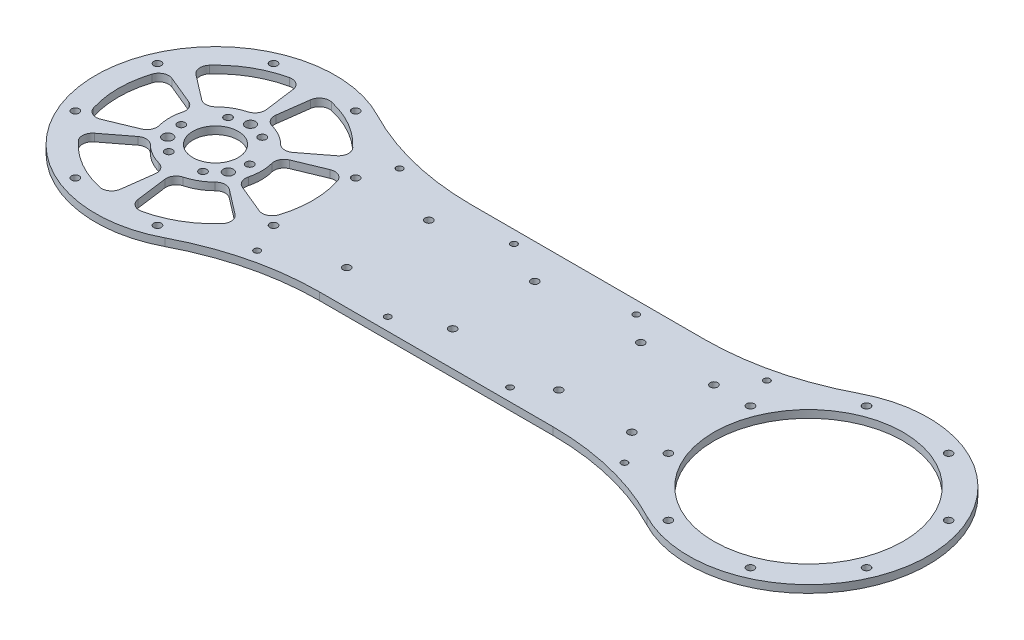
SolidWorks part; units mm, degrees
material "Hexcel AS4C (3000 丝)"
ref_plane "前视基准面" through (0, 0, 0) normal (0, 0, 1) x (1, 0, 0)
ref_plane "上视基准面" through (0, 0, 0) normal (0, 1, 0) x (1, 0, 0)
ref_plane "右视基准面" through (0, 0, 0) normal (1, 0, 0) x (0, 0, -1)
sketch "草图1" plane through (0, 0, 0) normal (0, 1, 0) x (1, 0, 0)
  line L0 (0, 0) -> (235, 0) construction
  line L1 (22, 42.0981) -> (22, -42.0981) construction
  line L2 (213, 42.0981) -> (213, -42.0981) construction
  line L3 (71.2712, 30) -> (163.7288, 30)
  line L4 (71.2712, -30) -> (163.7288, -30)
  line L14 (251.264, -39.2649) -> (274.2649, -16.264) construction
  line L15 (274.2649, -16.264) -> (274.2649, 16.264) construction
  line L16 (274.2649, 16.264) -> (251.264, 39.2649) construction
  line L17 (251.264, 39.2649) -> (218.736, 39.2649) construction
  line L18 (218.736, 39.2649) -> (195.7351, 16.264) construction
  line L19 (195.7351, 16.264) -> (195.7351, -16.264) construction
  line L20 (195.7351, -16.264) -> (218.736, -39.2649) construction
  line L21 (218.736, -39.2649) -> (251.264, -39.2649) construction
  line L30 (-16.264, 39.2649) -> (-39.2649, 16.264) construction
  line L31 (-39.2649, 16.264) -> (-39.2649, -16.264) construction
  line L32 (-39.2649, -16.264) -> (-16.264, -39.2649) construction
  line L33 (-16.264, -39.2649) -> (16.264, -39.2649) construction
  line L34 (16.264, -39.2649) -> (39.2649, -16.264) construction
  line L35 (39.2649, -16.264) -> (39.2649, 16.264) construction
  line L36 (39.2649, 16.264) -> (16.264, 39.2649) construction
  line L37 (16.264, 39.2649) -> (-16.264, 39.2649) construction
  line L38 (6.7839, -11.75) -> (13.5677, 0) construction
  line L39 (13.5677, 0) -> (6.7839, 11.75) construction
  line L40 (6.7839, 11.75) -> (-6.7839, 11.75) construction
  line L41 (-6.7839, 11.75) -> (-13.5677, 0) construction
  line L42 (-13.5677, 0) -> (-6.7839, -11.75) construction
  line L43 (-6.7839, -11.75) -> (6.7839, -11.75) construction
  line L44 (-12, -6.9282) -> (0, -13.8564) construction
  line L45 (0, -13.8564) -> (12, -6.9282) construction
  line L46 (12, -6.9282) -> (12, 6.9282) construction
  line L47 (12, 6.9282) -> (0, 13.8564) construction
  line L48 (0, 13.8564) -> (-12, 6.9282) construction
  line L49 (-12, 6.9282) -> (-12, -6.9282) construction
  circle A0 centre (0, 0) radius 47.5 construction
  circle A1 centre (235, 0) radius 47.5 construction
  arc A2 (22, 42.0981) -> (22, -42.0981) centre (0, 0) ccw
  arc A3 (213, 42.0981) -> (213, -42.0981) centre (235, 0) cw
  arc A4 (22, 42.0981) -> (71.2712, 30) centre (71.2712, 136.381) ccw
  arc A5 (22, -42.0981) -> (71.2712, -30) centre (71.2712, -136.381) cw
  arc A6 (163.7288, 30) -> (213, 42.0981) centre (163.7288, 136.381) ccw
  arc A7 (163.7288, -30) -> (213, -42.0981) centre (163.7288, -136.381) cw
  circle A8 centre (235, 0) radius 42.5 construction
  circle A9 centre (218.736, 39.2649) radius 1.5
  circle A10 centre (251.264, 39.2649) radius 1.5
  circle A11 centre (274.2649, 16.264) radius 1.5
  circle A12 centre (274.2649, -16.264) radius 1.5
  circle A13 centre (251.264, -39.2649) radius 1.5
  circle A14 centre (218.736, -39.2649) radius 1.5
  circle A15 centre (195.7351, -16.264) radius 1.5
  circle A16 centre (195.7351, 16.264) radius 1.5
  circle A17 centre (235, 0) radius 37.5
  circle A18 centre (0, 0) radius 42.5 construction
  circle A19 centre (-16.264, 39.2649) radius 1.5
  circle A20 centre (16.264, 39.2649) radius 1.5
  circle A21 centre (39.2649, 16.264) radius 1.5
  circle A22 centre (39.2649, -16.264) radius 1.5
  circle A23 centre (16.264, -39.2649) radius 1.5
  circle A24 centre (-16.264, -39.2649) radius 1.5
  circle A25 centre (-39.2649, -16.264) radius 1.5
  circle A26 centre (-39.2649, 16.264) radius 1.5
  circle A27 centre (0, 0) radius 9
  circle A28 centre (0, 0) radius 11.75 construction
  circle A29 centre (-6.7839, 11.75) radius 1.5
  circle A30 centre (6.7839, 11.75) radius 1.5
  circle A31 centre (13.5677, 0) radius 1.5
  circle A32 centre (6.7839, -11.75) radius 1.5
  circle A33 centre (-6.7839, -11.75) radius 1.5
  circle A34 centre (-13.5677, 0) radius 1.5
  circle A35 centre (0, 0) radius 12 construction
  circle A36 centre (0, 13.8564) radius 2
  circle A37 centre (-12, -6.9282) radius 2
  circle A38 centre (12, -6.9282) radius 2
  dimension "D2" = 95
  dimension "D6" = 85
  dimension "D7" = 3
  dimension "D8" = 75
  dimension "D9" = 85
  dimension "D10" = 3
  dimension "D11" = 18
  dimension "D12" = 23.5
  dimension "D13" = 3
  dimension "D15" = 4
  dimension "D1" = 235
  dimension "D3" = 22
  dimension "D4" = 22
  dimension "D5" = 60
  dimension "D14" = 24
extrude "凸台-拉伸1" add sketch "草图1" along normal blind 3
sketch "草图2" plane through (0, 0, 0) normal (0, -1, 0) x (1, 0, 0)
  circle A1 centre (0, 0) radius 9
  circle A2 centre (0, 0) radius 9
  circle A3 centre (235, 0) radius 29.6
  circle A4 centre (235, 0) radius 29.6
  circle A5 centre (218.736, -39.2649) radius 1.5
  circle A6 centre (218.736, -39.2649) radius 1.5
  circle A7 centre (251.264, -39.2649) radius 1.5
  circle A8 centre (251.264, -39.2649) radius 1.5
  circle A9 centre (251.264, 39.2649) radius 1.5
  circle A10 centre (251.264, 39.2649) radius 1.5
  circle A11 centre (274.2649, -16.264) radius 1.5
  circle A12 centre (274.2649, -16.264) radius 1.5
  circle A13 centre (274.2649, 16.264) radius 1.5
  circle A14 centre (274.2649, 16.264) radius 1.5
  circle A15 centre (195.7351, -16.264) radius 1.5
  circle A16 centre (195.7351, -16.264) radius 1.5
  circle A17 centre (195.7351, 16.264) radius 1.5
  circle A18 centre (195.7351, 16.264) radius 1.5
  circle A19 centre (218.736, 39.2649) radius 1.5
  circle A20 centre (218.736, 39.2649) radius 1.5
  circle A21 centre (-16.264, -39.2649) radius 1.5
  circle A22 centre (-16.264, -39.2649) radius 1.5
  circle A23 centre (16.264, -39.2649) radius 1.5
  circle A24 centre (16.264, -39.2649) radius 1.5
  circle A25 centre (39.2649, -16.264) radius 1.5
  circle A26 centre (39.2649, -16.264) radius 1.5
  circle A27 centre (39.2649, 16.264) radius 1.5
  circle A28 centre (39.2649, 16.264) radius 1.5
  circle A29 centre (16.264, 39.2649) radius 1.5
  circle A30 centre (16.264, 39.2649) radius 1.5
  circle A31 centre (-16.264, 39.2649) radius 1.5
  circle A32 centre (-16.264, 39.2649) radius 1.5
  circle A33 centre (-39.2649, 16.264) radius 1.5
  circle A34 centre (-39.2649, 16.264) radius 1.5
  circle A35 centre (-39.2649, -16.264) radius 1.5
  circle A36 centre (-39.2649, -16.264) radius 1.5
  circle A37 centre (6.7839, -11.75) radius 1.5
  circle A38 centre (6.7839, -11.75) radius 1.5
  circle A39 centre (13.5677, 0) radius 1.5
  circle A40 centre (13.5677, 0) radius 1.5
  circle A41 centre (-6.7839, -11.75) radius 1.5
  circle A42 centre (-6.7839, -11.75) radius 1.5
  circle A43 centre (-13.5677, 0) radius 1.5
  circle A44 centre (-13.5677, 0) radius 1.5
  circle A45 centre (6.7839, 11.75) radius 1.5
  circle A46 centre (6.7839, 11.75) radius 1.5
  circle A47 centre (-6.7839, 11.75) radius 1.5
  circle A48 centre (-6.7839, 11.75) radius 1.5
  circle A49 centre (93.2712, -25) radius 1.25
  circle A50 centre (93.2712, -25) radius 1.25
  circle A51 centre (93.2712, 25) radius 1.25
  circle A52 centre (93.2712, 25) radius 1.25
  circle A53 centre (190.2885, 28.213) radius 1.25
  circle A54 centre (190.2885, 28.213) radius 1.25
  circle A55 centre (141.7288, 25) radius 1.25
  circle A56 centre (141.7288, 25) radius 1.25
  circle A57 centre (44.7115, 28.213) radius 1.25
  circle A58 centre (44.7115, 28.213) radius 1.25
  circle A59 centre (44.7115, -28.213) radius 1.25
  circle A60 centre (44.7115, -28.213) radius 1.25
  circle A61 centre (190.2885, -28.213) radius 1.25
  circle A62 centre (190.2885, -28.213) radius 1.25
  circle A63 centre (141.7288, -25) radius 1.25
  circle A64 centre (141.7288, -25) radius 1.25
  dimension "D1" = 0
  dimension "D2" = 0
  dimension "D3" = 0
  dimension "D4" = 0
  dimension "D5" = 0
  dimension "D6" = 0
  dimension "D7" = 0
  dimension "D8" = 0
  dimension "D9" = 0
  dimension "D10" = 0
  dimension "D11" = 0
  dimension "D12" = 0
  dimension "D13" = 0
  dimension "D14" = 0
  dimension "D15" = 0
  dimension "D16" = 0
  dimension "D17" = 0
  dimension "D18" = 0
  dimension "D19" = 0
  dimension "D20" = 0
  dimension "D21" = 0
  dimension "D22" = 0
  dimension "D23" = 0
  dimension "D24" = 0
  dimension "D25" = 0
  dimension "D26" = 0
  dimension "D27" = 0
  dimension "D28" = 0
  dimension "D29" = 0
  dimension "D30" = 0
  dimension "D31" = 0
  dimension "D32" = 0
extrude "切除-拉伸1" cut sketch "草图2" against normal blind 10 contours A54 | A56 | A52 | A58 | A60 | A50 | A64 | A62
sketch "草图3" plane through (0, 0, 0) normal (0, -1, 0) x (1, 0, 0)
  line L2 (-3.4947, -34.2058) -> (-1.8862, -21.9887)
  line L3 (-18.0997, -12.6279) -> (-27.8758, -20.1294)
  line L4 (-3.4947, -34.2058) -> (-1.8862, -21.9887)
  line L5 (-18.0997, -12.6279) -> (-27.8758, -20.1294)
  line L6 (-31.3704, -14.0764) -> (-19.9859, -9.3608)
  line L7 (-19.9859, 9.3608) -> (-31.3704, 14.0764)
  line L8 (-31.3704, -14.0764) -> (-19.9859, -9.3608)
  line L9 (-19.9859, 9.3608) -> (-31.3704, 14.0764)
  line L10 (-27.8758, 20.1294) -> (-18.0997, 12.6279)
  line L11 (-1.8862, 21.9887) -> (-3.4947, 34.2058)
  line L12 (-27.8758, 20.1294) -> (-18.0997, 12.6279)
  line L13 (-1.8862, 21.9887) -> (-3.4947, 34.2058)
  line L14 (3.4947, 34.2058) -> (1.8862, 21.9887)
  line L15 (18.0997, 12.6279) -> (27.8758, 20.1294)
  line L16 (3.4947, 34.2058) -> (1.8862, 21.9887)
  line L17 (18.0997, 12.6279) -> (27.8758, 20.1294)
  line L18 (31.3704, 14.0764) -> (19.9859, 9.3608)
  line L19 (19.9859, -9.3608) -> (31.3704, -14.0764)
  line L20 (31.3704, 14.0764) -> (19.9859, 9.3608)
  line L21 (19.9859, -9.3608) -> (31.3704, -14.0764)
  line L22 (27.8758, -20.1294) -> (18.0997, -12.6279)
  line L23 (1.8862, -21.9887) -> (3.4947, -34.2058)
  line L24 (27.8758, -20.1294) -> (18.0997, -12.6279)
  line L25 (1.8862, -21.9887) -> (3.4947, -34.2058)
  circle A1 centre (-12, 6.9282) radius 3
  circle A2 centre (-12, 6.9282) radius 3
  circle A3 centre (-13.5677, 0) radius 2.5
  circle A4 centre (-13.5677, 0) radius 2.5
  circle A5 centre (6.7839, 11.75) radius 2.5
  circle A6 centre (6.7839, 11.75) radius 2.5
  circle A7 centre (6.7839, -11.75) radius 2.5
  circle A8 centre (6.7839, -11.75) radius 2.5
  circle A9 centre (0, 0) radius 10
  circle A10 centre (0, 0) radius 10
  circle A11 centre (-39.2649, 16.264) radius 2.5
  circle A12 centre (-39.2649, 16.264) radius 2.5
  circle A13 centre (16.264, 39.2649) radius 2.5
  circle A14 centre (16.264, 39.2649) radius 2.5
  circle A15 centre (39.2649, -16.264) radius 2.5
  circle A16 centre (39.2649, -16.264) radius 2.5
  circle A17 centre (-16.264, -39.2649) radius 2.5
  circle A18 centre (-16.264, -39.2649) radius 2.5
  circle A19 centre (16.264, -39.2649) radius 2.5
  circle A20 centre (16.264, -39.2649) radius 2.5
  circle A21 centre (39.2649, 16.264) radius 2.5
  circle A22 centre (39.2649, 16.264) radius 2.5
  circle A23 centre (-16.264, 39.2649) radius 2.5
  arc A24 (-8.3254, -37.5891) -> (-3.4947, -34.2058) centre (-7.4604, -33.6837) ccw
  arc A25 (-28.3904, -26.0045) -> (-8.3254, -37.5891) centre (0, 0) ccw
  arc A26 (-27.8758, -20.1294) -> (-28.3904, -26.0045) centre (-25.4407, -23.3028) ccw
  arc A27 (-12.8485, -12.9606) -> (-18.0997, -12.6279) centre (-15.6646, -15.8013) ccw
  arc A28 (-12.8485, -12.9606) -> (-4.8, -17.6075) centre (0, 0) ccw
  arc A29 (-1.8862, -21.9887) -> (-4.8, -17.6075) centre (-5.852, -21.4666) ccw
  arc A30 (-8.3254, -37.5891) -> (-3.4947, -34.2058) centre (-7.4604, -33.6837) ccw
  arc A31 (-28.3904, -26.0045) -> (-8.3254, -37.5891) centre (0, 0) ccw
  arc A32 (-27.8758, -20.1294) -> (-28.3904, -26.0045) centre (-25.4407, -23.3028) ccw
  arc A33 (-12.8485, -12.9606) -> (-18.0997, -12.6279) centre (-15.6646, -15.8013) ccw
  arc A34 (-12.8485, -12.9606) -> (-4.8, -17.6075) centre (0, 0) ccw
  arc A35 (-1.8862, -21.9887) -> (-4.8, -17.6075) centre (-5.852, -21.4666) ccw
  circle A36 centre (-16.264, 39.2649) radius 2.5
  circle A37 centre (-39.2649, -16.264) radius 2.5
  circle A38 centre (-39.2649, -16.264) radius 2.5
  circle A39 centre (-6.7839, -11.75) radius 2.5
  circle A40 centre (-6.7839, -11.75) radius 2.5
  circle A41 centre (13.5677, 0) radius 2.5
  circle A42 centre (13.5677, 0) radius 2.5
  circle A43 centre (-6.7839, 11.75) radius 2.5
  circle A44 centre (-6.7839, 11.75) radius 2.5
  circle A45 centre (0, -13.8564) radius 3
  circle A46 centre (0, -13.8564) radius 3
  circle A47 centre (12, 6.9282) radius 3
  circle A48 centre (12, 6.9282) radius 3
  arc A54 (-36.7158, -11.5845) -> (-31.3704, -14.0764) centre (-32.9012, -10.3809) ccw
  arc A55 (-36.7158, 11.5845) -> (-36.7158, -11.5845) centre (0, 0) ccw
  arc A56 (-31.3704, 14.0764) -> (-36.7158, 11.5845) centre (-32.9012, 10.3809) ccw
  arc A57 (-17.6485, 4.6468) -> (-19.9859, 9.3608) centre (-21.5167, 5.6653) ccw
  arc A58 (-17.6485, 4.6468) -> (-17.6485, -4.6468) centre (0, 0) ccw
  arc A59 (-19.9859, -9.3608) -> (-17.6485, -4.6468) centre (-21.5167, -5.6653) ccw
  arc A60 (-36.7158, -11.5845) -> (-31.3704, -14.0764) centre (-32.9012, -10.3809) ccw
  arc A61 (-36.7158, 11.5845) -> (-36.7158, -11.5845) centre (0, 0) ccw
  arc A62 (-31.3704, 14.0764) -> (-36.7158, 11.5845) centre (-32.9012, 10.3809) ccw
  arc A63 (-17.6485, 4.6468) -> (-19.9859, 9.3608) centre (-21.5167, 5.6653) ccw
  arc A64 (-17.6485, 4.6468) -> (-17.6485, -4.6468) centre (0, 0) ccw
  arc A65 (-19.9859, -9.3608) -> (-17.6485, -4.6468) centre (-21.5167, -5.6653) ccw
  arc A66 (-28.3904, 26.0045) -> (-27.8758, 20.1294) centre (-25.4407, 23.3028) ccw
  arc A67 (-8.3254, 37.5891) -> (-28.3904, 26.0045) centre (0, 0) ccw
  arc A68 (-3.4947, 34.2058) -> (-8.3254, 37.5891) centre (-7.4604, 33.6837) ccw
  arc A69 (-4.8, 17.6075) -> (-1.8862, 21.9887) centre (-5.852, 21.4666) ccw
  arc A70 (-4.8, 17.6075) -> (-12.8485, 12.9606) centre (0, 0) ccw
  arc A71 (-18.0997, 12.6279) -> (-12.8485, 12.9606) centre (-15.6646, 15.8013) ccw
  arc A72 (-28.3904, 26.0045) -> (-27.8758, 20.1294) centre (-25.4407, 23.3028) ccw
  arc A73 (-8.3254, 37.5891) -> (-28.3904, 26.0045) centre (0, 0) ccw
  arc A74 (-3.4947, 34.2058) -> (-8.3254, 37.5891) centre (-7.4604, 33.6837) ccw
  arc A75 (-4.8, 17.6075) -> (-1.8862, 21.9887) centre (-5.852, 21.4666) ccw
  arc A76 (-4.8, 17.6075) -> (-12.8485, 12.9606) centre (0, 0) ccw
  arc A77 (-18.0997, 12.6279) -> (-12.8485, 12.9606) centre (-15.6646, 15.8013) ccw
  arc A78 (8.3254, 37.5891) -> (3.4947, 34.2058) centre (7.4604, 33.6837) ccw
  arc A79 (28.3904, 26.0045) -> (8.3254, 37.5891) centre (0, 0) ccw
  arc A80 (27.8758, 20.1294) -> (28.3904, 26.0045) centre (25.4407, 23.3028) ccw
  arc A81 (12.8485, 12.9606) -> (18.0997, 12.6279) centre (15.6646, 15.8013) ccw
  arc A82 (12.8485, 12.9606) -> (4.8, 17.6075) centre (0, 0) ccw
  arc A83 (1.8862, 21.9887) -> (4.8, 17.6075) centre (5.852, 21.4666) ccw
  arc A84 (8.3254, 37.5891) -> (3.4947, 34.2058) centre (7.4604, 33.6837) ccw
  arc A85 (28.3904, 26.0045) -> (8.3254, 37.5891) centre (0, 0) ccw
  arc A86 (27.8758, 20.1294) -> (28.3904, 26.0045) centre (25.4407, 23.3028) ccw
  arc A87 (12.8485, 12.9606) -> (18.0997, 12.6279) centre (15.6646, 15.8013) ccw
  arc A88 (12.8485, 12.9606) -> (4.8, 17.6075) centre (0, 0) ccw
  arc A89 (1.8862, 21.9887) -> (4.8, 17.6075) centre (5.852, 21.4666) ccw
  arc A90 (36.7158, 11.5845) -> (31.3704, 14.0764) centre (32.9012, 10.3809) ccw
  arc A91 (36.7158, -11.5845) -> (36.7158, 11.5845) centre (0, 0) ccw
  arc A92 (31.3704, -14.0764) -> (36.7158, -11.5845) centre (32.9012, -10.3809) ccw
  arc A93 (17.6485, -4.6468) -> (19.9859, -9.3608) centre (21.5167, -5.6653) ccw
  arc A94 (17.6485, -4.6468) -> (17.6485, 4.6468) centre (0, 0) ccw
  arc A95 (19.9859, 9.3608) -> (17.6485, 4.6468) centre (21.5167, 5.6653) ccw
  arc A96 (36.7158, 11.5845) -> (31.3704, 14.0764) centre (32.9012, 10.3809) ccw
  arc A97 (36.7158, -11.5845) -> (36.7158, 11.5845) centre (0, 0) ccw
  arc A98 (31.3704, -14.0764) -> (36.7158, -11.5845) centre (32.9012, -10.3809) ccw
  arc A99 (17.6485, -4.6468) -> (19.9859, -9.3608) centre (21.5167, -5.6653) ccw
  arc A100 (17.6485, -4.6468) -> (17.6485, 4.6468) centre (0, 0) ccw
  arc A101 (19.9859, 9.3608) -> (17.6485, 4.6468) centre (21.5167, 5.6653) ccw
  arc A102 (28.3904, -26.0045) -> (27.8758, -20.1294) centre (25.4407, -23.3028) ccw
  arc A103 (8.3254, -37.5891) -> (28.3904, -26.0045) centre (0, 0) ccw
  arc A104 (3.4947, -34.2058) -> (8.3254, -37.5891) centre (7.4604, -33.6837) ccw
  arc A105 (4.8, -17.6075) -> (1.8862, -21.9887) centre (5.852, -21.4666) ccw
  arc A106 (4.8, -17.6075) -> (12.8485, -12.9606) centre (0, 0) ccw
  arc A107 (18.0997, -12.6279) -> (12.8485, -12.9606) centre (15.6646, -15.8013) ccw
  arc A108 (28.3904, -26.0045) -> (27.8758, -20.1294) centre (25.4407, -23.3028) ccw
  arc A109 (8.3254, -37.5891) -> (28.3904, -26.0045) centre (0, 0) ccw
  arc A110 (3.4947, -34.2058) -> (8.3254, -37.5891) centre (7.4604, -33.6837) ccw
  arc A111 (4.8, -17.6075) -> (1.8862, -21.9887) centre (5.852, -21.4666) ccw
  arc A112 (4.8, -17.6075) -> (12.8485, -12.9606) centre (0, 0) ccw
  arc A113 (18.0997, -12.6279) -> (12.8485, -12.9606) centre (15.6646, -15.8013) ccw
  dimension "D1" = 0
  dimension "D2" = 0
  dimension "D3" = 0
  dimension "D4" = 0
  dimension "D5" = 0
  dimension "D6" = 0
  dimension "D7" = 0
  dimension "D8" = 0
  dimension "D9" = 0
  dimension "D10" = 0
  dimension "D11" = 0
  dimension "D12" = 0
  dimension "D13" = 0
  dimension "D14" = 0
  dimension "D15" = 0
  dimension "D16" = 0
  dimension "D17" = 0
  dimension "D18" = 0
  dimension "D19" = 0
  dimension "D20" = 0
  dimension "D21" = 0
  dimension "D22" = 0
  dimension "D23" = 0
  dimension "D24" = 0
extrude "切除-拉伸2" cut sketch "草图3" against normal blind 10 contours L16 A89 A88 A87 L17 A86 A85 A84 | L20 A101 A100 A99 L21 A98 A97 A96 | L24 A113 A112 A111 L25 A110 A109 A108 | L4 A35 A34 A33 L5 A32 A31 A30 | L8 A65 A64 A63 L9 A62 A61 A60 | L12 A77 A76 A75 L13 A74 A73 A72
sketch "草图4" plane through (0, 3, 0) normal (0, 1, 0) x (1, 0, 0)
  circle A16 centre (68.2649, -16.264) radius 1.5 construction
  circle A17 centre (110.2649, -16.264) radius 1.5 construction
  circle A18 centre (181.2649, -16.264) radius 1.5 construction
  circle A19 centre (152.2649, -16.264) radius 1.5 construction
  circle A20 centre (181.2649, 16.264) radius 1.5 construction
  circle A21 centre (152.2649, 16.264) radius 1.5 construction
  circle A22 centre (110.2649, 16.264) radius 1.5 construction
  circle A23 centre (68.2649, 16.264) radius 1.5 construction
  circle A24 centre (68.2649, -16.264) radius 1.5
  circle A25 centre (110.2649, -16.264) radius 1.5
  circle A26 centre (181.2649, -16.264) radius 1.5
  circle A27 centre (152.2649, -16.264) radius 1.5
  circle A28 centre (181.2649, 16.264) radius 1.5
  circle A29 centre (152.2649, 16.264) radius 1.5
  circle A30 centre (110.2649, 16.264) radius 1.5
  circle A31 centre (68.2649, 16.264) radius 1.5
extrude "切除-拉伸3" cut sketch "草图4" against normal through all both and the other way through all
